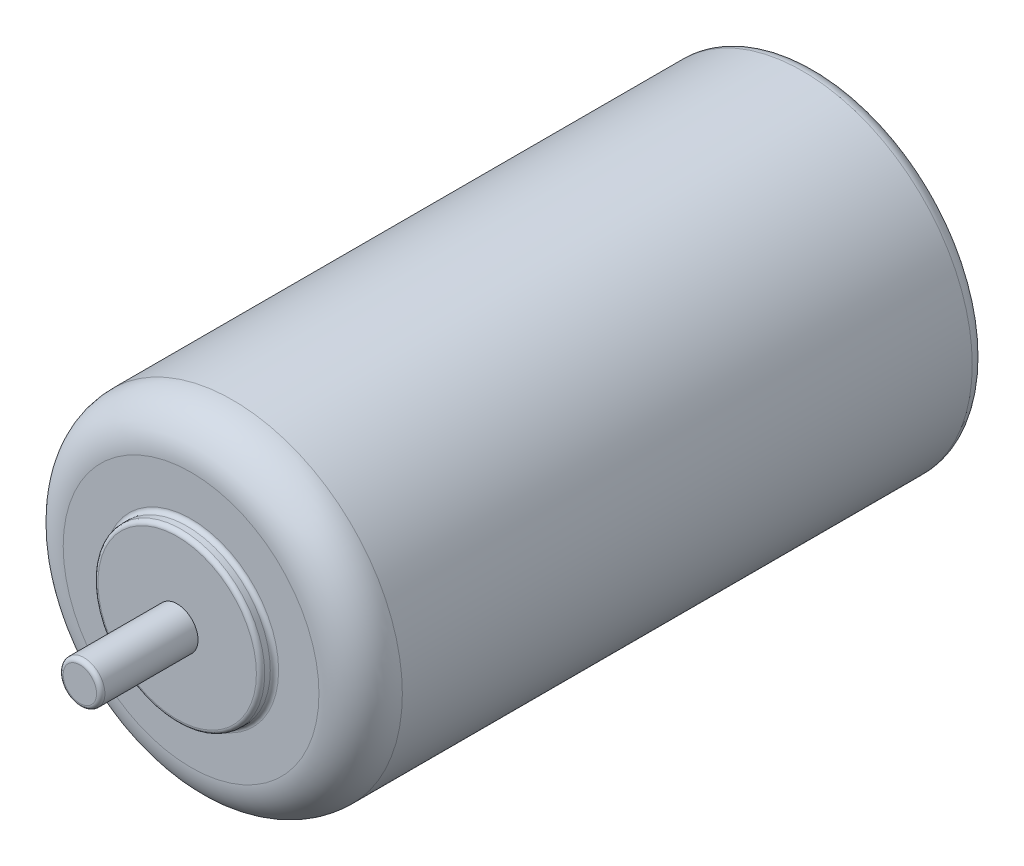
SolidWorks part; units mm, degrees
ref_plane "Front Plane" through (0, 0, 0) normal (0, 0, 1) x (1, 0, 0)
ref_plane "Top Plane" through (0, 0, 0) normal (0, 1, 0) x (1, 0, 0)
ref_plane "Right Plane" through (0, 0, 0) normal (1, 0, 0) x (0, 0, -1)
sketch "Sketch1" plane through (0, 0, 0) normal (0, 0, 1) x (1, 0, 0)
  circle A0 centre (0, 0) radius 12.2
  dimension "D1" = 24.4
extrude "Boss-Extrude1" add sketch "Sketch1" along normal blind 45 contours A0
ref_plane "Plane1" through (0, 0, 45) normal (0, 0, 1) x (1, 0, 0)
sketch "Sketch2" plane through (0, 0, 45) normal (0, 0, 1) x (1, 0, 0)
  circle A0 centre (0, 0) radius 6
  dimension "D1" = 12
extrude "Boss-Extrude2" add sketch "Sketch2" along normal blind 1 contours A0
sketch "Sketch3" plane through (0, 0, 45) normal (0, 0, 1) x (1, 0, 0)
  circle A0 centre (0, 0) radius 1.5
  dimension "D1" = 3
extrude "Boss-Extrude3" add sketch "Sketch3" along normal blind 8
ref_plane "Plane2" through (0, 0, 53) normal (0, 0, 1) x (1, 0, 0)
fillet "Fillet1" radius 3 1 edges at (12.2, 0, 45)
fillet "Fillet2" radius 1 1 edges at (12.2, 0, 0)
fillet "Fillet3" radius 0.3 2 edges at (6, 0, 46) (6, 0, 45)
fillet "Fillet4" radius 0.3 1 edges at (1.5, 0, 53)
